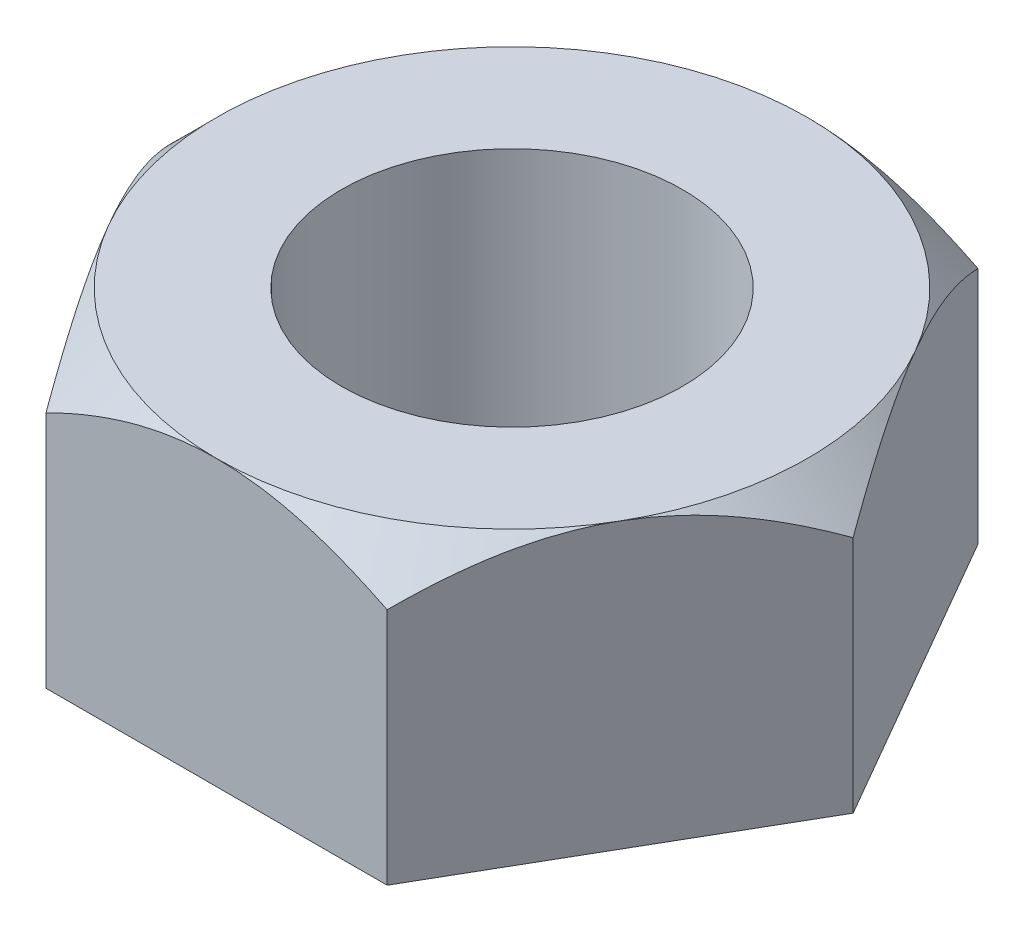
SolidWorks part; units mm, degrees
ref_plane "Front Plane" through (0, 0, 0) normal (0, 0, 1) x (1, 0, 0)
ref_plane "Top Plane" through (0, 0, 0) normal (0, 1, 0) x (1, 0, 0)
ref_plane "Right Plane" through (0, 0, 0) normal (1, 0, 0) x (0, 0, -1)
sketch "Sketch1" plane through (0, 0, 0) normal (0, 1, 0) x (1, 0, 0)
  line L0 (-32.5338, 0) -> (27.78, 0) construction
  line L1 (0, 25.5517) -> (0, -17.9753) construction
  line L3 (6, -10.3923) -> (12, 0)
  line L4 (12, 0) -> (6, 10.3923)
  line L5 (6, 10.3923) -> (-6, 10.3923)
  line L6 (-6, 10.3923) -> (-12, 0)
  line L7 (-12, 0) -> (-6, -10.3923)
  line L8 (-6, -10.3923) -> (6, -10.3923)
  circle A0 centre (0, 0) radius 10.3923 construction
  dimension "D1" = 24
extrude "Boss-Extrude1" add sketch "Sketch1" along normal blind 10
sketch "Sketch2" plane through (0, 10, 0) normal (0, 1, 0) x (1, 0, 0)
  circle A0 centre (0, 0) radius 10.3923
extrude "Cut-Extrude2" cut sketch "Sketch2" against normal blind 12 draft 45 flip side to cut
sketch "Sketch3" plane through (0, 10, 0) normal (0, 1, 0) x (1, 0, 0)
  circle A0 centre (0, 0) radius 6
  dimension "D1" = 12
extrude "Cut-Extrude3" cut sketch "Sketch3" against normal up to next
